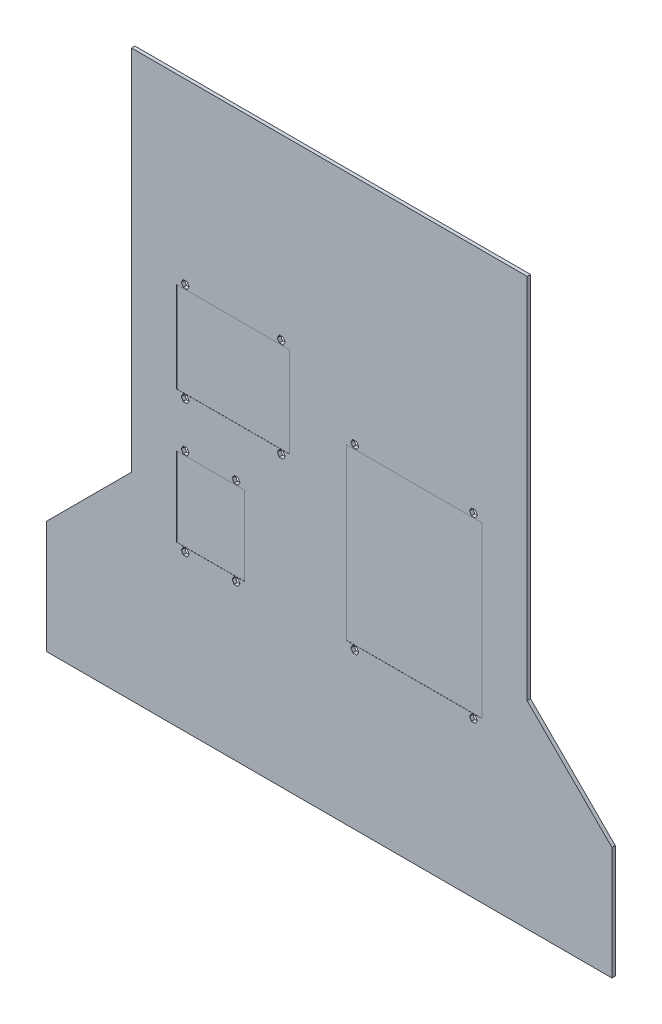
SolidWorks part; units mm, degrees
ref_plane "Front Plane" through (0, 0, 0) normal (0, 0, 1) x (1, 0, 0)
ref_plane "Top Plane" through (0, 0, 0) normal (0, 1, 0) x (1, 0, 0)
ref_plane "Right Plane" through (0, 0, 0) normal (1, 0, 0) x (0, 0, -1)
sketch "Sketch1" plane through (0, 0, 0) normal (0, 0, 1) x (1, 0, 0)
  line L0 (-250, 0) -> (-250, 100)
  line L1 (-250, 100) -> (-175, 175)
  line L2 (-175, 175) -> (-175, 500)
  line L3 (-175, 500) -> (175, 500)
  line L4 (175, 500) -> (175, 175)
  line L5 (175, 175) -> (250, 100)
  line L6 (250, 100) -> (250, 0)
  line L7 (250, 0) -> (-250, 0)
  line L8 (-175, 175) -> (175, 175) construction
  line L9 (-250, 100) -> (250, 100) construction
  line L10 (0, 0) -> (0, 100) construction
  line L11 (0, 100) -> (0, 175) construction
  line L12 (0, 175) -> (0, 500) construction
  point P5 (0, 0)
  dimension "D1" = 500
  dimension "D2" = 500
  dimension "D3" = 100
  dimension "D4" = 45
  dimension "D5" = 350
extrude "Boss-Extrude1" add sketch "Sketch1" along normal blind 3
sketch "Sketch3" plane through (0, 0, 0) normal (0, 0, 1) x (1, 0, 0)
  line L1 (-135, 338.75) -> (-35, 338.75)
  line L2 (-135, 338.75) -> (-135, 258.75)
  line L3 (-135, 258.75) -> (-35, 258.75)
  line L4 (-35, 338.75) -> (-35, 258.75)
  line L5 (-135, 211.25) -> (-75, 211.25)
  line L6 (-135, 211.25) -> (-135, 141.25)
  line L7 (-135, 141.25) -> (-75, 141.25)
  line L8 (-75, 211.25) -> (-75, 141.25)
  line L9 (135, 141.25) -> (15, 141.25)
  line L10 (135, 141.25) -> (135, 291.25)
  line L11 (135, 291.25) -> (15, 291.25)
  line L12 (15, 141.25) -> (15, 291.25)
  line L24 (-127.5, 215) -> (-127.5, 137.5) construction
  line L25 (-127.5, 137.5) -> (-82.5, 137.5) construction
  line L26 (-82.5, 137.5) -> (-82.5, 215) construction
  line L27 (-82.5, 215) -> (-127.5, 215) construction
  line L28 (22.5, 137.5) -> (127.5, 137.5) construction
  line L29 (127.5, 137.5) -> (127.5, 295) construction
  line L30 (127.5, 295) -> (22.5, 295) construction
  line L31 (22.5, 295) -> (22.5, 137.5) construction
  line L32 (-127.5, 255) -> (-42.5, 255) construction
  line L33 (-42.5, 255) -> (-42.5, 342.5) construction
  line L34 (-42.5, 342.5) -> (-127.5, 342.5) construction
  line L35 (-127.5, 342.5) -> (-127.5, 255) construction
  line L36 (-212.5, 137.5) -> (212.5, 137.5) construction
  line L37 (-175, 175) -> (-250, 100) construction
  line L38 (250, 100) -> (175, 175) construction
  line L39 (-175, 175) -> (-135, 175) construction
  line L40 (-175, 500) -> (-175, 175) construction
  line L41 (175, 175) -> (135, 175) construction
  circle A0 centre (-127.5, 137.5) radius 1.75
  circle A1 centre (-82.5, 137.5) radius 1.75
  circle A2 centre (-127.5, 215) radius 1.75
  circle A3 centre (-82.5, 215) radius 1.75
  circle A4 centre (-127.5, 255) radius 1.75
  circle A5 centre (-127.5, 342.5) radius 1.75
  circle A6 centre (-42.5, 255) radius 1.75
  circle A7 centre (-42.5, 342.5) radius 1.75
  circle A8 centre (22.5, 137.5) radius 1.75
  circle A9 centre (127.5, 137.5) radius 1.75
  circle A10 centre (22.5, 295) radius 1.75
  circle A11 centre (127.5, 295) radius 1.75
  dimension "D1" = 3.5
  dimension "D2" = 45
  dimension "D3" = 77.5
  dimension "D4" = 60
  dimension "D5" = 70
  dimension "D6" = 7.5
  dimension "D7" = 3.75
  dimension "D8" = 105
  dimension "D9" = 157.5
  dimension "D10" = 150
  dimension "D11" = 120
  dimension "D12" = 7.5
  dimension "D13" = 3.75
  dimension "D14" = 85
  dimension "D15" = 87.5
  dimension "D16" = 80
  dimension "D17" = 100
  dimension "D18" = 7.5
  dimension "D19" = 3.75
  dimension "D20" = 40
  dimension "D21" = 40
  dimension "D22" = 40
extrude "Cut-Extrude3" cut sketch "Sketch3" against normal blind 0.1 from surface at 3 contours L4 L1 L2 L3 | L12 L9 L10 L11 | L8 L5 L6 L7 starting at face at (0, 193.75, 3)
sketch "Sketch4" plane through (0, 0, 0) normal (0, 0, -1) x (-1, 0, 0)
  line L1 (-20.7679, 140.5) -> (-24.2321, 140.5)
  line L2 (-24.2321, 140.5) -> (-25.9641, 137.5)
  line L3 (-25.9641, 137.5) -> (-24.2321, 134.5)
  line L4 (-24.2321, 134.5) -> (-20.7679, 134.5)
  line L5 (-20.7679, 134.5) -> (-19.0359, 137.5)
  line L6 (-19.0359, 137.5) -> (-20.7679, 140.5)
  line L7 (-129.2321, 134.5) -> (-125.7679, 134.5)
  line L8 (-125.7679, 134.5) -> (-124.0359, 137.5)
  line L9 (-124.0359, 137.5) -> (-125.7679, 140.5)
  line L10 (-125.7679, 140.5) -> (-129.2321, 140.5)
  line L11 (-129.2321, 140.5) -> (-130.9641, 137.5)
  line L12 (-130.9641, 137.5) -> (-129.2321, 134.5)
  line L13 (79.0359, 137.5) -> (80.7679, 134.5)
  line L14 (80.7679, 134.5) -> (84.2321, 134.5)
  line L15 (84.2321, 134.5) -> (85.9641, 137.5)
  line L16 (85.9641, 137.5) -> (84.2321, 140.5)
  line L17 (84.2321, 140.5) -> (80.7679, 140.5)
  line L18 (80.7679, 140.5) -> (79.0359, 137.5)
  line L19 (129.2321, 134.5) -> (130.9641, 137.5)
  line L20 (130.9641, 137.5) -> (129.2321, 140.5)
  line L21 (129.2321, 140.5) -> (125.7679, 140.5)
  line L22 (125.7679, 140.5) -> (124.0359, 137.5)
  line L23 (124.0359, 137.5) -> (125.7679, 134.5)
  line L24 (125.7679, 134.5) -> (129.2321, 134.5)
  line L25 (129.2321, 218) -> (125.7679, 218)
  line L26 (125.7679, 218) -> (124.0359, 215)
  line L27 (124.0359, 215) -> (125.7679, 212)
  line L28 (125.7679, 212) -> (129.2321, 212)
  line L29 (129.2321, 212) -> (130.9641, 215)
  line L30 (130.9641, 215) -> (129.2321, 218)
  line L31 (80.7679, 218) -> (79.0359, 215)
  line L32 (79.0359, 215) -> (80.7679, 212)
  line L33 (80.7679, 212) -> (84.2321, 212)
  line L34 (84.2321, 212) -> (85.9641, 215)
  line L35 (85.9641, 215) -> (84.2321, 218)
  line L36 (84.2321, 218) -> (80.7679, 218)
  line L37 (125.7679, 252) -> (129.2321, 252)
  line L38 (129.2321, 252) -> (130.9641, 255)
  line L39 (130.9641, 255) -> (129.2321, 258)
  line L40 (129.2321, 258) -> (125.7679, 258)
  line L41 (125.7679, 258) -> (124.0359, 255)
  line L42 (124.0359, 255) -> (125.7679, 252)
  line L43 (44.2321, 252) -> (45.9641, 255)
  line L44 (45.9641, 255) -> (44.2321, 258)
  line L45 (44.2321, 258) -> (40.7679, 258)
  line L46 (40.7679, 258) -> (39.0359, 255)
  line L47 (39.0359, 255) -> (40.7679, 252)
  line L48 (40.7679, 252) -> (44.2321, 252)
  line L49 (-130.9641, 295) -> (-129.2321, 292)
  line L50 (-129.2321, 292) -> (-125.7679, 292)
  line L51 (-125.7679, 292) -> (-124.0359, 295)
  line L52 (-124.0359, 295) -> (-125.7679, 298)
  line L53 (-125.7679, 298) -> (-129.2321, 298)
  line L54 (-129.2321, 298) -> (-130.9641, 295)
  line L55 (-19.0359, 295) -> (-20.7679, 298)
  line L56 (-20.7679, 298) -> (-24.2321, 298)
  line L57 (-24.2321, 298) -> (-25.9641, 295)
  line L58 (-25.9641, 295) -> (-24.2321, 292)
  line L59 (-24.2321, 292) -> (-20.7679, 292)
  line L60 (-20.7679, 292) -> (-19.0359, 295)
  line L61 (40.7679, 345.5) -> (39.0359, 342.5)
  line L62 (39.0359, 342.5) -> (40.7679, 339.5)
  line L63 (40.7679, 339.5) -> (44.2321, 339.5)
  line L64 (44.2321, 339.5) -> (45.9641, 342.5)
  line L65 (45.9641, 342.5) -> (44.2321, 345.5)
  line L66 (44.2321, 345.5) -> (40.7679, 345.5)
  line L67 (129.2321, 345.5) -> (125.7679, 345.5)
  line L68 (125.7679, 345.5) -> (124.0359, 342.5)
  line L69 (124.0359, 342.5) -> (125.7679, 339.5)
  line L70 (125.7679, 339.5) -> (129.2321, 339.5)
  line L71 (129.2321, 339.5) -> (130.9641, 342.5)
  line L72 (130.9641, 342.5) -> (129.2321, 345.5)
  line L75 (127.5, 137.5) -> (82.5, 137.5) construction
  line L76 (-22.5, 137.5) -> (-127.5, 137.5) construction
  line L77 (-127.5, 295) -> (-22.5, 295) construction
  line L78 (42.5, 342.5) -> (127.5, 342.5) construction
  line L79 (127.5, 255) -> (42.5, 255) construction
  line L80 (82.5, 215) -> (127.5, 215) construction
  circle A0 centre (-22.5, 137.5) radius 3 construction
  circle A1 centre (-127.5, 137.5) radius 3 construction
  circle A2 centre (82.5, 137.5) radius 3 construction
  circle A3 centre (127.5, 137.5) radius 3 construction
  circle A4 centre (127.5, 215) radius 3 construction
  circle A5 centre (82.5, 215) radius 3 construction
  circle A6 centre (127.5, 255) radius 3 construction
  circle A7 centre (42.5, 255) radius 3 construction
  circle A8 centre (-127.5, 295) radius 3 construction
  circle A9 centre (-22.5, 295) radius 3 construction
  circle A10 centre (42.5, 342.5) radius 3 construction
  circle A11 centre (127.5, 342.5) radius 3 construction
  point P100 (-127.5, 173.7144)
  point P109 (-109.422, 295)
  point P111 (-127.5, 274.058)
  point P112 (-22.5, 264.4754)
  point P113 (-52.4944, 295)
  point P114 (57.688, 342.5)
  point P115 (-22.5, 173.7144)
  point P116 (82.5, 164.2073)
  point P117 (99.4731, 137.5)
  point P118 (-22.5, 92.0623)
  point P119 (116.6075, 137.5)
  point P122 (0, 0)
  point P123 (0, 0)
  point P124 (0, 0)
  point P125 (-107.0339, 137.5)
  point P128 (-46.0692, 137.5)
  point P129 (0, 0)
  point P131 (0, 0)
  point P134 (109.6573, 342.5)
  point P135 (65.5269, 255)
  point P138 (104.6991, 255)
  point P139 (99.4731, 215)
  point P142 (108.104, 215)
  point P143 (109.6573, 137.5)
  dimension "D1" = 6
extrude "Cut-Extrude4" cut sketch "Sketch4" against normal through all
